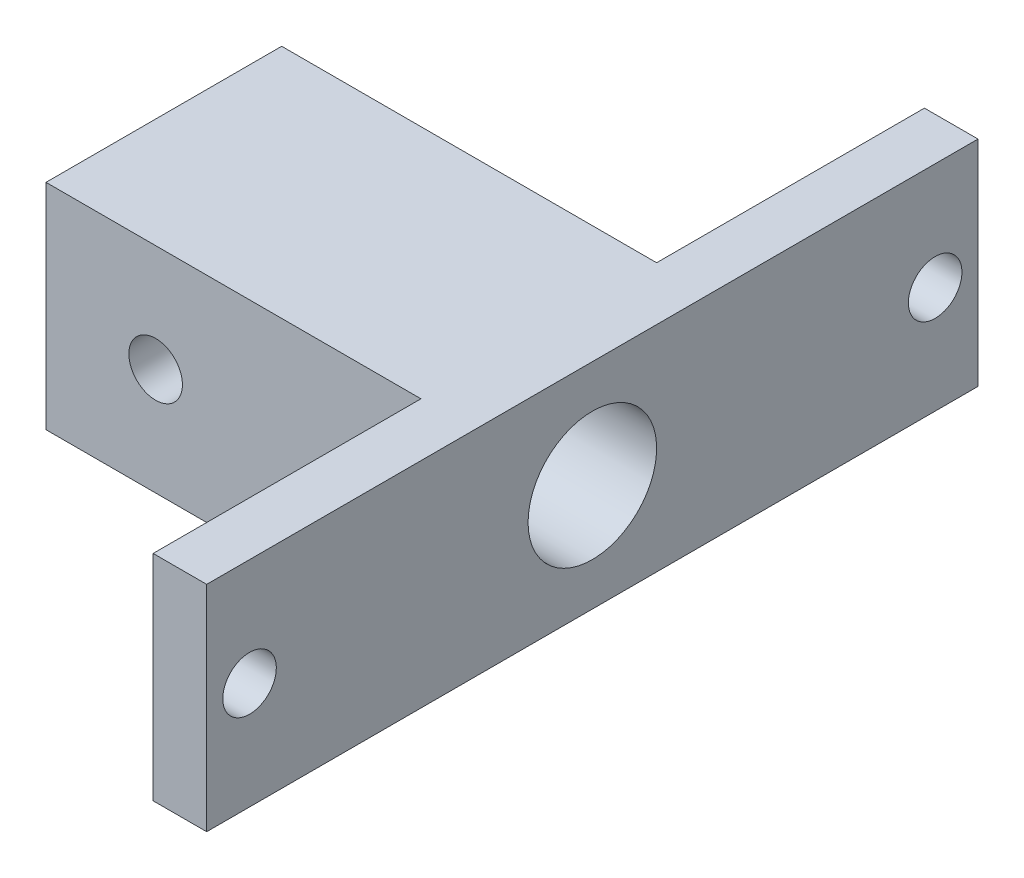
SolidWorks part; units mm, degrees
material "6061-T4 (SS)"
ref_plane "Front Plane" through (0, 0, 0) normal (0, 0, 1) x (1, 0, 0)
ref_plane "Top Plane" through (0, 0, 0) normal (0, 1, 0) x (1, 0, 0)
ref_plane "Right Plane" through (0, 0, 0) normal (1, 0, 0) x (0, 0, -1)
sketch "Sketch1" plane through (0, 0, 0) normal (0, 0, 1) x (1, 0, 0)
  line L1 (-12.7, 6.35) -> (12.7, 6.35)
  line L2 (-12.7, 6.35) -> (-12.7, -6.35)
  line L3 (-12.7, -6.35) -> (12.7, -6.35)
  line L4 (12.7, 6.35) -> (12.7, -6.35)
  line L5 (-12.7, 6.35) -> (12.7, -6.35) construction
  line L6 (-12.7, -6.35) -> (12.7, 6.35) construction
  point P0 (0, 0)
  dimension "D1" = 25.4
  dimension "D3" = 12.7
extrude "Boss-Extrude1" add sketch "Sketch1" along normal mid plane 13.97
ref_plane "Plane1" through (-12.7, 0, 0) normal (-1, 0, 0) x (0, 0, 1)
sketch "Sketch2" plane through (-12.7, 0, 0) normal (-1, 0, 0) x (0, 0, 1)
  line L1 (-2.54, 3.81) -> (2.54, 3.81)
  line L2 (-2.54, 3.81) -> (-2.54, -3.81)
  line L3 (-2.54, -3.81) -> (2.54, -3.81)
  line L4 (2.54, 3.81) -> (2.54, -3.81)
  line L5 (-2.54, 3.81) -> (2.54, -3.81) construction
  line L6 (-2.54, -3.81) -> (2.54, 3.81) construction
  point P0 (0, 0)
  dimension "D1" = 5.08
  dimension "D2" = 7.62
extrude "Cut-Extrude1" [suppressed] cut sketch "Sketch2" against normal through all
ref_plane "Plane4" through (0, 0, -6.985) normal (0, 0, -1) x (-1, 0, 0)
sketch "Sketch3" plane through (0, 0, -6.985) normal (0, 0, -1) x (-1, 0, 0)
  line L0 (12.7, -6.35) -> (-12.7, -6.35) construction
  line L1 (-12.7, 6.35) -> (-9.525, 6.35)
  line L2 (-12.7, 6.35) -> (-12.7, -6.35)
  line L3 (-12.7, -6.35) -> (-9.525, -6.35)
  line L4 (-9.525, 6.35) -> (-9.525, -6.35)
  dimension "D1" = 3.175
extrude "Boss-Extrude2" add sketch "Sketch3" along normal blind 15.875
ref_plane "Plane5" through (0, 0, 6.985) normal (0, 0, 1) x (1, 0, 0)
sketch "Sketch4" plane through (0, 0, 6.985) normal (0, 0, 1) x (1, 0, 0)
  line L0 (12.7, 6.35) -> (-12.7, 6.35) construction
  line L1 (12.7, -6.35) -> (9.525, -6.35)
  line L2 (12.7, -6.35) -> (12.7, 6.35)
  line L3 (12.7, 6.35) -> (9.525, 6.35)
  line L4 (9.525, -6.35) -> (9.525, 6.35)
  dimension "D1" = 3.175
extrude "Boss-Extrude3" add sketch "Sketch4" along normal blind 15.875
sketch "Sketch5" plane through (9.525, 0, 0) normal (-1, 0, 0) x (0, 0, 1)
  line L0 (-22.86, -6.35) -> (-22.86, 6.35) construction
  line L3 (22.86, 6.35) -> (22.86, -6.35) construction
  circle A0 centre (-20.32, 0) radius 1.5875
  circle A1 centre (20.32, 0) radius 1.5875
  dimension "D1" = 3.175
  dimension "D2" = 3.175
  dimension "D3" = 2.54
  dimension "D4" = 2.54
extrude "Cut-Extrude2" cut sketch "Sketch5" against normal through all
sketch "Sketch6" plane through (-12.7, 0, 0) normal (-1, 0, 0) x (0, 0, 1)
  circle A0 centre (0, 0) radius 3.81
  dimension "D1" = 7.62
extrude "Cut-Extrude3" cut sketch "Sketch6" against normal through all
sketch "Sketch7" plane through (0, 0, 6.985) normal (0, 0, 1) x (1, 0, 0)
  line L0 (9.525, 6.35) -> (9.525, -6.35) construction
  circle A0 centre (-6.2005, 0) radius 1.5875
  dimension "D1" = 3.175
  dimension "D2" = 15.7255
extrude "Cut-Extrude4" cut sketch "Sketch7" against normal through all
